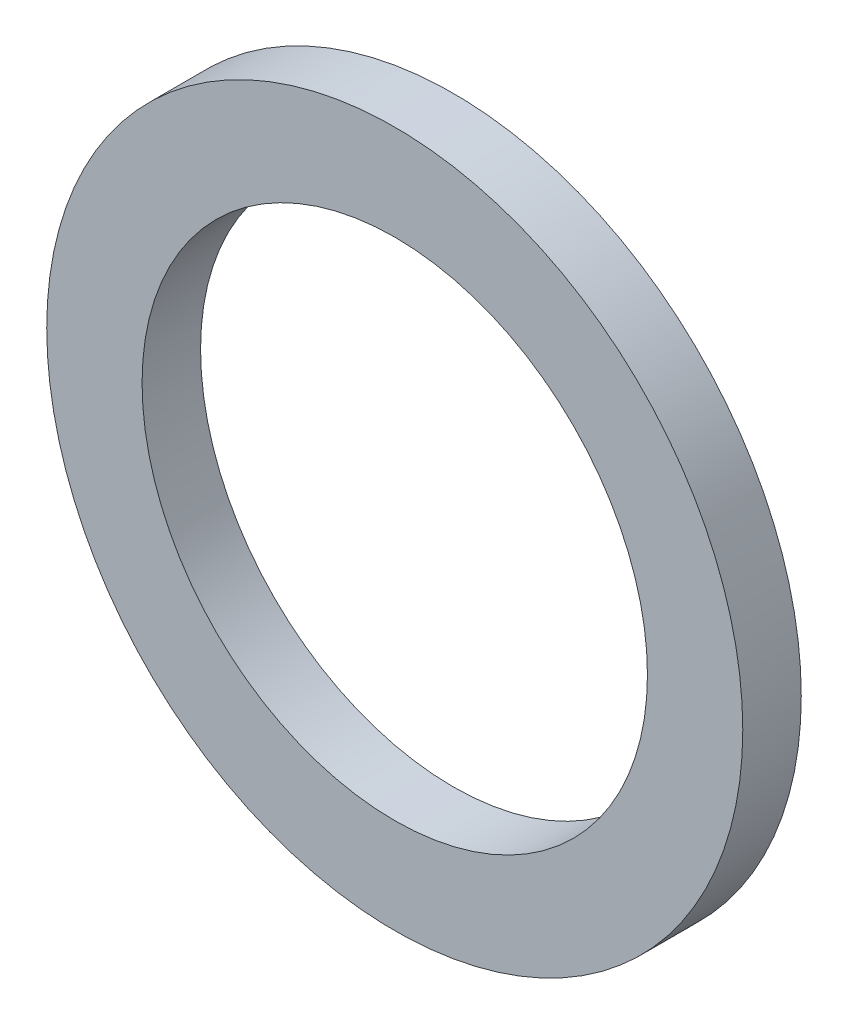
SolidWorks part; units mm, degrees
ref_plane "Ön Düzlem" through (0, 0, 0) normal (0, 0, 1) x (1, 0, 0)
ref_plane "Üst Düzlem" through (0, 0, 0) normal (0, 1, 0) x (1, 0, 0)
ref_plane "Sağ Düzlem" through (0, 0, 0) normal (1, 0, 0) x (0, 0, -1)
sketch "Çizim1" plane through (0, 0, 0) normal (0, 0, 1) x (1, 0, 0)
  circle A0 centre (0, 0) radius 11.9
  circle A1 centre (0, 0) radius 8.64
  dimension "D1" = 23.8
  dimension "D2" = 17.28
extrude "Yükseklik-Ekstrüzyon1" add sketch "Çizim1" along normal blind 2
